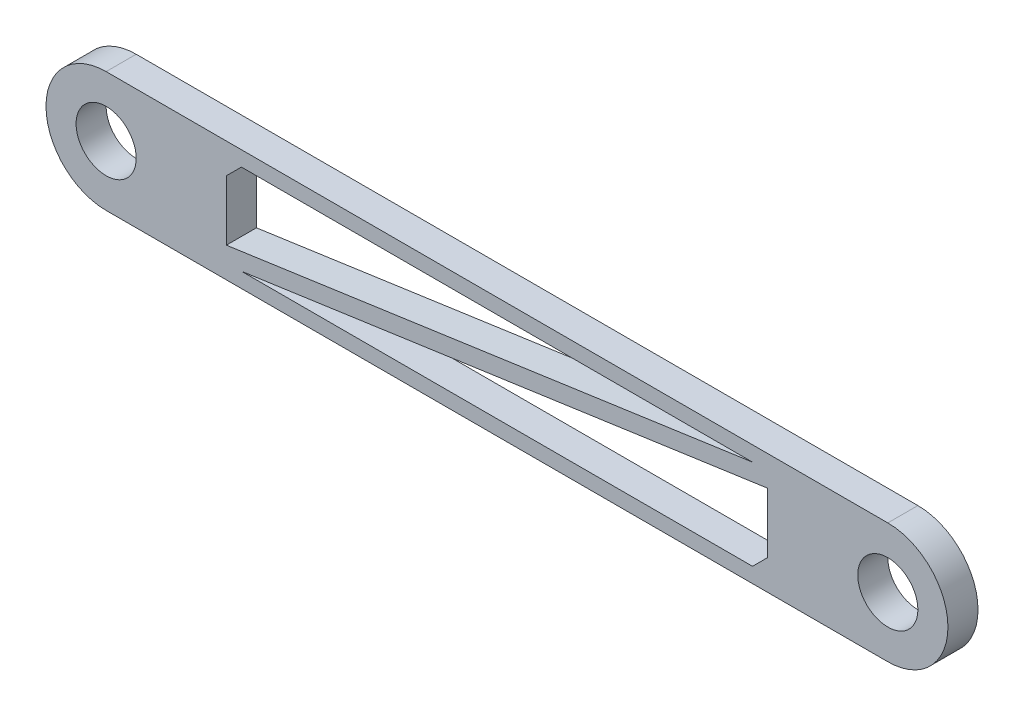
SolidWorks part; units mm, degrees
ref_plane "Front Plane" through (0, 0, 0) normal (0, 0, 1) x (1, 0, 0)
ref_plane "Top Plane" through (0, 0, 0) normal (0, 1, 0) x (1, 0, 0)
ref_plane "Right Plane" through (0, 0, 0) normal (1, 0, 0) x (0, 0, -1)
sketch "Sketch1" plane through (0, 0, 0) normal (0, 0, 1) x (1, 0, 0)
  line L0 (150, 0) -> (130, 0) construction
  line L1 (-130, -20) -> (130, -20)
  line L3 (-130, 20) -> (130, 20)
  line L5 (-90, 10) -> (-85, 15)
  line L6 (-85, -15) -> (85, -15)
  line L7 (-150, 0) -> (-130, 0) construction
  line L8 (-90, -10) -> (-90, 10)
  line L9 (-85, 15) -> (85, 15)
  line L10 (90, -10) -> (90, 10)
  line L11 (-90, -15) -> (90, 15) construction
  line L12 (-90, 15) -> (90, -15) construction
  line L14 (85, -15) -> (90, -10)
  line L16 (-85, -15) -> (90, 10)
  line L17 (85, 15) -> (-90, -10)
  arc A0 (130, -20) -> (130, 20) centre (130, 0) ccw
  arc A1 (-130, 20) -> (-130, -20) centre (-130, 0) ccw
  circle A2 centre (130, 0) radius 10
  circle A3 centre (-130, 0) radius 10
  point P0 (0, 0)
  point P2 (0, 0)
  dimension "D15" = 20
  dimension "D16" = 20
  dimension "D1" = 20
  dimension "D2" = 5
  dimension "D3" = 20
  dimension "D4" = 20
  dimension "D5" = 60
  dimension "D6" = 150
  dimension "D7" = 5
  dimension "D8" = 5
  dimension "D9" = 5
  dimension "D10" = 5
  dimension "D11" = 5
  dimension "D12" = 5
  dimension "D13" = 5
  dimension "D14" = 5
extrude "Boss-Extrude1" add sketch "Sketch1" along normal blind 10
